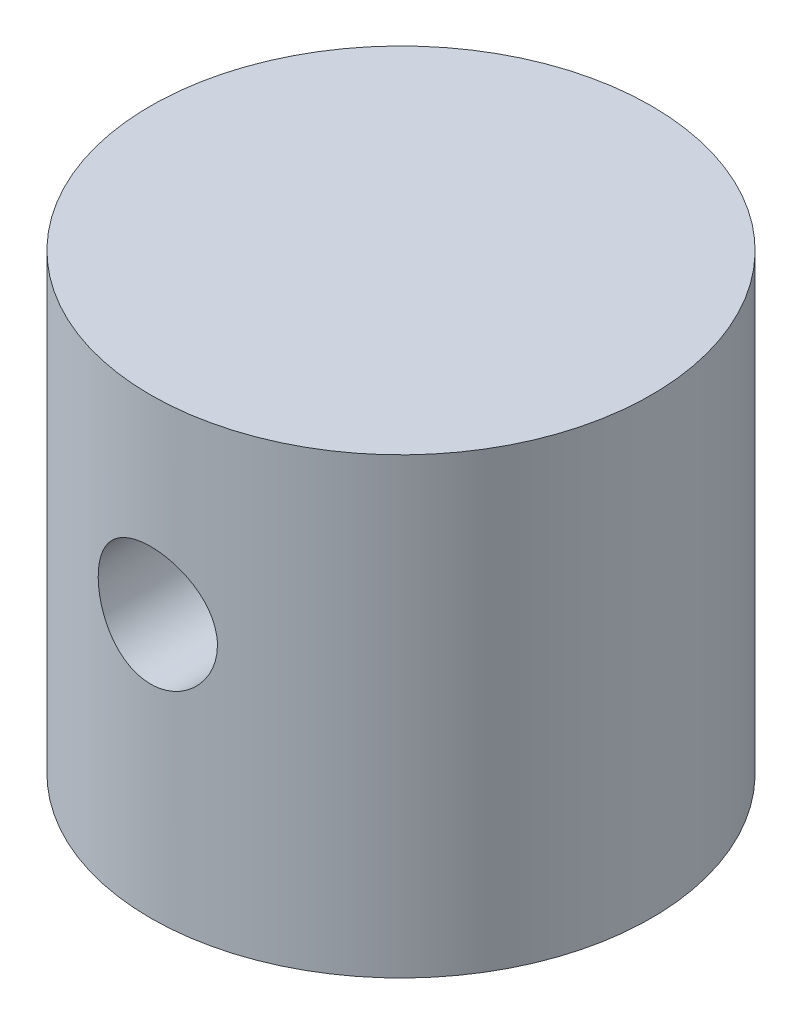
SolidWorks part; units mm, degrees
material "Gray Cast Iron"
ref_plane "Front Plane" through (0, 0, 0) normal (0, 0, 1) x (1, 0, 0)
ref_plane "Top Plane" through (0, 0, 0) normal (0, 1, 0) x (1, 0, 0)
ref_plane "Right Plane" through (0, 0, 0) normal (1, 0, 0) x (0, 0, -1)
sketch "Sketch1" plane through (0, 0, 0) normal (0, 1, 0) x (1, 0, 0)
  circle A0 centre (0, 0) radius 10.5
  dimension "D1" = 21
extrude "Boss-Extrude1" add sketch "Sketch1" along normal blind 19
sketch "Sketch2" plane through (0, 0, 0) normal (0, -1, 0) x (1, 0, 0)
  circle A0 centre (0, 0) radius 10
  dimension "D1" = 20
extrude "Cut-Extrude1" cut sketch "Sketch2" against normal blind 6
sketch "Sketch3" plane through (0, 6, 0) normal (0, -1, 0) x (1, 0, 0)
  line L0 (3, 0) -> (-3, 0) construction
  line L1 (10.45, 0) -> (-10.45, 0) construction
  line L2 (3, -6) -> (-3, -6)
  line L3 (3, 6) -> (-3, 6)
  arc A0 (3, -6) -> (3, 6) centre (3, 0) ccw
  arc A1 (-3, 6) -> (-3, -6) centre (-3, 0) ccw
  point P5 (0, 0)
  dimension "D1" = 12
  dimension "D2" = 6
extrude "Cut-Extrude2" cut sketch "Sketch3" against normal blind 11
sketch "Sketch4" plane through (0, 0, 0) normal (0, 0, 1) x (1, 0, 0)
  line L0 (0, -10.45) -> (0, 10.45) construction
  line L1 (11.55, 0) -> (-11.55, 0) construction
  circle A0 centre (0, 11) radius 2.5
  dimension "D1" = 5
  dimension "D2" = 11
extrude "Cut-Extrude3" cut sketch "Sketch4" against normal through all both and the other way through all
